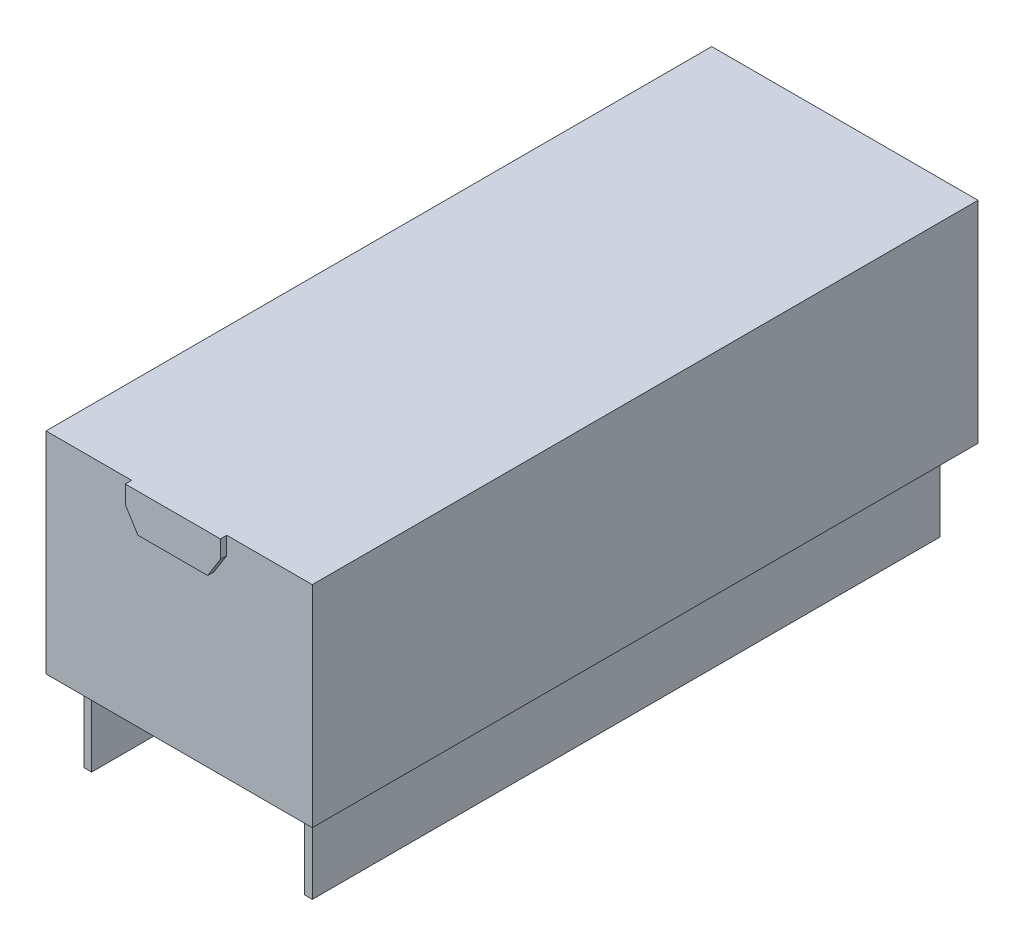
SolidWorks part; units mm, degrees
ref_plane "Front Plane" through (0, 0, 0) normal (0, 0, 1) x (1, 0, 0)
ref_plane "Top Plane" through (0, 0, 0) normal (0, 1, 0) x (1, 0, 0)
ref_plane "Right Plane" through (0, 0, 0) normal (1, 0, 0) x (0, 0, -1)
sketch "Sketch1" plane through (0, 0, 0) normal (0, 1, 0) x (1, 0, 0)
  line L1 (-10.5, 26.25) -> (10.5, 26.25)
  line L2 (-10.5, 26.25) -> (-10.5, -26.25)
  line L3 (-10.5, -26.25) -> (10.5, -26.25)
  line L4 (10.5, 26.25) -> (10.5, -26.25)
  line L5 (-10.5, 26.25) -> (10.5, -26.25) construction
  line L6 (-10.5, -26.25) -> (10.5, 26.25) construction
  point P0 (0, 0)
  dimension "D1" = 21
  dimension "D2" = 52.5
extrude "Boss-Extrude1" add sketch "Sketch1" along normal blind 16.6
sketch "Sketch2" plane through (0, 0, 26.25) normal (0, 0, 1) x (1, 0, 0)
  line L0 (-10.5, 16.6) -> (10.5, 16.6) construction
  line L1 (-3.75, 16.6) -> (3.75, 16.6) construction
  line L2 (-3.75, 16.6) -> (-3.75, 13.6) construction
  line L3 (-3.75, 13.6) -> (3.75, 13.6) construction
  line L4 (3.75, 16.6) -> (3.75, 13.6) construction
  line L5 (-10.5, 16.6) -> (10.5, 16.6) construction
  line L6 (-3.75, 16.6) -> (-3.75, 15.2)
  line L7 (3.75, 16.6) -> (3.75, 15.2)
  line L8 (-3.75, 16.6) -> (3.75, 16.6)
  line L9 (-3.75, 15.2) -> (-2.75, 13.6)
  line L10 (-2.75, 13.6) -> (2.75, 13.6)
  line L11 (2.75, 13.6) -> (3.75, 15.2)
  point P10 (0, 13.6)
  point P11 (0, 16.6)
  point P16 (0, 0)
  point P17 (0, 0)
  point P18 (-3.75, 14.4461)
  point P19 (-3.1206, 13.6)
  dimension "D1" = 3
  dimension "D2" = 7.5
  dimension "D3" = 5.5
  dimension "D4" = 1.4
extrude "Boss-Extrude2" add sketch "Sketch2" along normal blind 0.5
sketch "Sketch3" plane through (0, 0, 0) normal (0, -1, 0) x (1, 0, 0)
  line L0 (0, 26.25) -> (0, -26.25) construction
  line L1 (-9, 24.75) -> (-8.4, 24.75)
  line L2 (-9, 24.75) -> (-9, -24.75)
  line L3 (-9, 0) -> (-8.4, 0)
  line L4 (-8.4, 24.75) -> (-8.4, -24.75)
  line L5 (-10.5, 26.25) -> (10.5, 26.25) construction
  line L6 (10.5, -26.25) -> (-10.5, -26.25) construction
  line L7 (0, 0) -> (-10.5, 0) construction
  line L8 (-10.5, -26.25) -> (-10.5, 26.25) construction
  line L9 (-9, -24.75) -> (-8.4, -24.75)
  line L10 (9, 24.75) -> (8.4, 24.75)
  line L11 (9, -24.75) -> (8.4, -24.75)
  line L12 (9, 24.75) -> (9, -24.75)
  line L13 (8.4, 24.75) -> (8.4, -24.75)
  point P8 (-8.4, 0)
  dimension "D1" = 1.5
  dimension "D2" = 0.6
  dimension "D3" = 1.5
extrude "Boss-Extrude3" add sketch "Sketch3" along normal blind 6.4 contours L4 L9 L2 L1 | L13 L11 L12 L10
